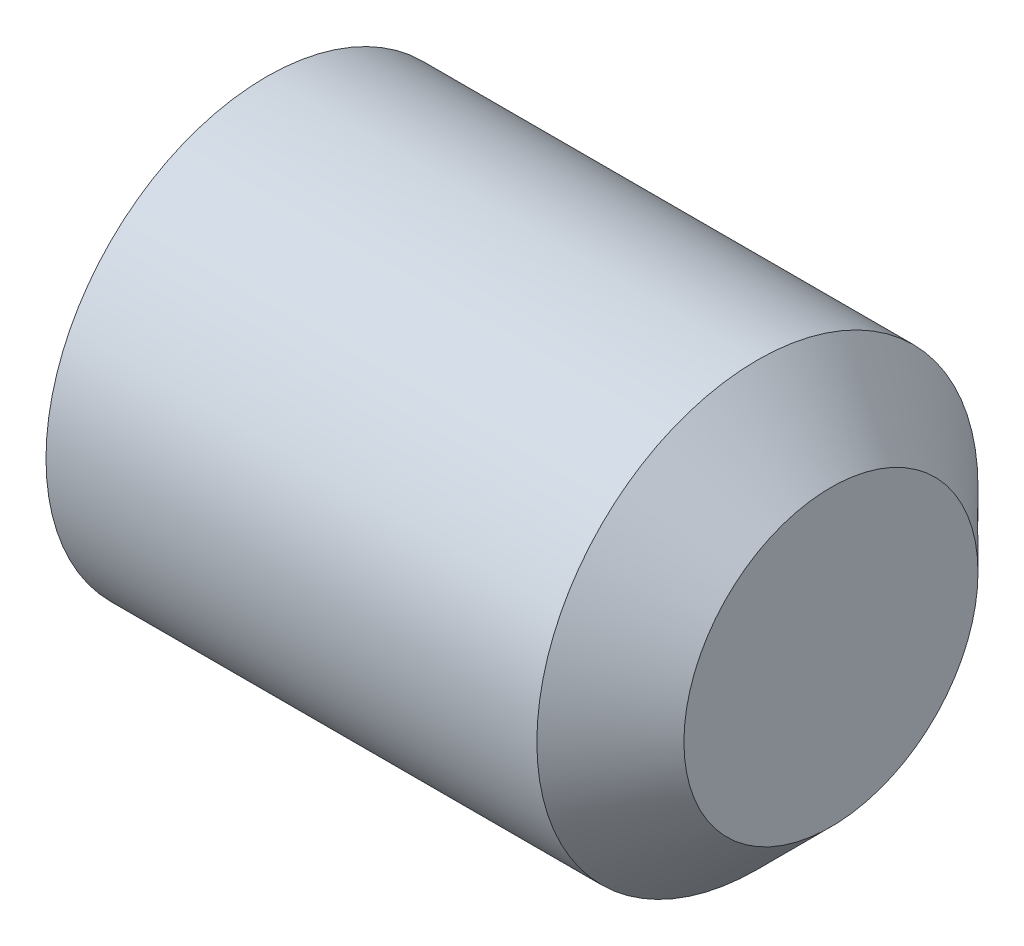
SolidWorks part; units mm, degrees
revolve "BaseBody" add sketch "BodySke" angle 360 about L5
sketch "BodySke" plane through (0, 0, 0) normal (0, 0, 1) x (1, 0, 0)
  line L0 (0, 0) -> (0, 1.2195)
  line L1 (0, 1.2195) -> (0.1619, 1.5)
  line L2 (0.1619, 1.5) -> (3.5, 1.5)
  line L3 (3.5, 1.5) -> (4, 1)
  line L4 (4, 0) -> (0, 0)
  line L5 (-12.7, 0) -> (88.9, 0) construction
  line L6 (4, 1) -> (4, 0)
  line L7 (4, 1) -> (4, 10.525) construction
  line L8 (0, -1.2195) -> (0.1619, -1.5) construction
  line L9 (0.5, 15.875) -> (0.5, -3.175) construction
  line L10 (3.5, -1.5) -> (4, -1) construction
  dimension "Diameter" = 3
  dimension "Drive_ch_ang" = 60
  dimension "Minor_dia" = 2.439
  dimension "Cup_nose_ang" = 45
  dimension "Cup_dia" = 2
  dimension "Length" = 4
  dimension "Advance" = 0.5
cosmetic thread "ThreadCosmetic" [suppressed] parameters "Thread_minor"=2.439
ref_plane "Plane1" through (0, 0, 0) normal (0, 0, 1) x (1, 0, 0)
ref_plane "Plane2" through (0, 0, 0) normal (0, 1, 0) x (1, 0, 0)
ref_plane "Plane3" through (0, 0, 0) normal (1, 0, 0) x (0, 0, -1)
other "Configuration Table"
sketch "Sketch2" plane through (0, 0, 0) normal (-1, 0, 0) x (0, 0, 1)
  line L0 (0.433, 0.75) -> (-0.433, 0.75)
  line L1 (-0.433, 0.75) -> (-0.866, 0)
  line L2 (0.433, 0.75) -> (0.866, 0)
  line L3 (0.433, -0.75) -> (0.866, 0)
  line L4 (0.433, -0.75) -> (-0.433, -0.75)
  line L5 (-0.433, -0.75) -> (-0.866, 0)
  dimension "Hex_size" = 1.5
  dimension "D2" = 0.75
  dimension "D3" = 0.75
extrude "Hex" cut sketch "Sketch2" against normal blind 2.1
sketch "Sketch4" plane through (0, 4.7709, -0.5249) normal (-1, 0, 0) x (0, 0, 1)
  line L0 (0.5249, -4.7709) -> (1.3124, -4.7709)
  line L1 (0.5249, -4.7709) -> (6.6732, -1.2211) construction
  line L2 (0.5249, -4.7709) -> (0.9186, -4.0889)
  line L3 (1.153, -4.6137) -> (1.2782, -4.5415)
  line L4 (0.975, -4.3054) -> (1.1002, -4.2332)
  arc A0 (1.153, -4.6137) -> (0.975, -4.3054) centre (0.5249, -4.7709) ccw
  arc A1 (1.3124, -4.7709) -> (1.2782, -4.5415) centre (0.5249, -4.7709) ccw
  arc A2 (0.9186, -4.0889) -> (1.1002, -4.2332) centre (0.5249, -4.7709) cw
  circle A3 centre (0.5249, -4.7709) radius 0.6475 construction
  circle A4 centre (0.5249, -4.7709) radius 0.7875 construction
  dimension "Spline_n_dim" = 1.295
  dimension "Spline_m_dim" = 1.575
  dimension "D1" = 30
  dimension "Spline_a_dim" = 60
  dimension "Spline_p_dim" = 0.356
  dimension "D3" = 0.178
extrude "Spline6" [suppressed] cut sketch "Sketch4" against normal blind 1.2
pattern_circular "CirPattern1" [suppressed] count 6 every 60 about axis through (-12.7, 0, 0) along (1, 0, 0)
sketch "Sketch5" plane through (0, 0.6556, 6.6316) normal (-1, 0, 0) x (0, 0, 1)
  line L0 (-6.6316, -0.6556) -> (-5.8441, -0.6556)
  line L1 (-6.6316, -0.6556) -> (-1.6115, 4.3645) construction
  line L2 (-6.6316, -0.6556) -> (-6.6316, 0.1319)
  line L3 (-6.0479, -0.3236) -> (-5.9633, -0.239)
  line L4 (-6.2996, -0.0719) -> (-6.215, 0.0127)
  line L5 (-6.2996, -0.0719) -> (-6.0479, -0.3236)
  arc A1 (-5.8441, -0.6556) -> (-5.9633, -0.239) centre (-6.6316, -0.6556) ccw
  arc A2 (-6.6316, 0.1319) -> (-6.215, 0.0127) centre (-6.6316, -0.6556) cw
  circle A3 centre (-6.6316, -0.6556) radius 0.6475 construction
  circle A4 centre (-6.6316, -0.6556) radius 0.7875 construction
  dimension "Spline_n_dim" = 1.295
  dimension "Spline_m_dim" = 1.575
  dimension "Spline_p_dim" = 0.356
  dimension "D3" = 0.178
  dimension "D1" = 45
  dimension "Spline_a_dim" = 90
extrude "Spline4" [suppressed] cut sketch "Sketch5" against normal blind 1.2
pattern_circular "CirPattern2" [suppressed] count 4 every 90 about axis through (-12.7, 0, 0) along (1, 0, 0)
sketch "ThdSchSke" plane through (0, 0, 0) normal (0, 0, 1) x (1, 0, 0)
  line L0 (0.1619, -1.2195) -> (-0.0345, -1.5)
  line L1 (0.1619, -1.2195) -> (0.3584, -1.5)
  line L2 (0.3584, -1.5) -> (0.3584, -1.875)
  line L3 (-3.175, 0) -> (5.1513, 0) construction
  line L4 (0.1619, 1.5) -> (0.1619, -1.5) construction
  line L5 (0.3584, -1.875) -> (-0.0345, -1.875)
  line L6 (-0.0345, -1.875) -> (-0.0345, -1.5)
  dimension "Thread_minor" = 2.439
  dimension "Diameter" = 3
revolve "ThreadSchematic" [suppressed] cut sketch "ThdSchSke" angle 360 about L3
pattern_linear "ThdSchPat" [suppressed]
equation "\"D2@Sketch2\" = \"Hex_size@Sketch2\" / 2"
equation "\"D3@Sketch2\" = \"Hex_size@Sketch2\" / 2"
equation "\"Thread_minor@ThreadCosmetic\" = \"Minor_dia@BodySke\""
equation "\"D1@Sketch4\" = \"Spline_a_dim@Sketch4\" / 2"
equation "\"D3@Sketch4\" = \"Spline_p_dim@Sketch4\" / 2"
equation "\"D2@CirPattern1\" = \"Spline_a_dim@Sketch4\""
equation "\"Num_teeth@CirPattern1\" = 360 / \"D2@CirPattern1\""
equation "\"Spline_a_dim@Sketch5\" = 90"
equation "\"Spline_p_dim@Sketch5\" = \"Spline_p_dim@Sketch4\""
equation "\"Spline_m_dim@Sketch5\" = \"Spline_m_dim@Sketch4\""
equation "\"Spline_n_dim@Sketch5\" = \"Spline_n_dim@Sketch4\""
equation "\"D1@Sketch5\" = \"Spline_a_dim@Sketch5\" / 2"
equation "\"D3@Sketch5\" = \"Spline_p_dim@Sketch5\" / 2"
equation "\"Key_eng@Spline4\" = \"Key_eng@Spline6\""
equation "\"Thread_minor@ThdSchSke\" = \"Thread_minor@ThreadCosmetic\""
equation "\"Diameter@ThdSchSke\" = \"Diameter@BodySke\""
equation "\"Overcut@ThdSchSke\" = \"Diameter@BodySke\" * 1.25"
equation "\"Num_threads@ThdSchPat\" = int( (\"Length@BodySke\" - ( ( ( \"Diameter@BodySke\" - \"Minor_dia@BodySke\" ) * 0.5 ) / tan( \"Drive_ch_ang@BodySke\" * 0.017453292 ) ) - ( ( ( \"Diameter@BodySke\" - \"Cup_dia@BodySke\" ) * 0.5 ) * tan( \"Cup_nose_ang@BodySke\" * 0.017453292 ) ) ) / \"Advance@BodySke\" + 0.999 )  + 1"
equation "\"Advance@ThdSchPat\" = (\"Length@BodySke\" - ( ( ( \"Diameter@BodySke\" - \"Minor_dia@BodySke\" ) * 0.5 ) / tan( \"Drive_ch_ang@BodySke\" * 0.017453292 ) ) - ( ( ( \"Diameter@BodySke\" - \"Cup_dia@BodySke\" ) * 0.5 ) * tan( \"Cup_nose_ang@BodySke\" * 0.017453292 ) ) ) /  (\"Num_threads@ThdSchPat\" - 1) 'relax it"
equation "' \"Num_threads@ThdSchPat\" = \"Num_threads@ThdSchPat\" - sgn( \"Num_threads@ThdSchPat\" - 1) '---chamfered tips only---"
